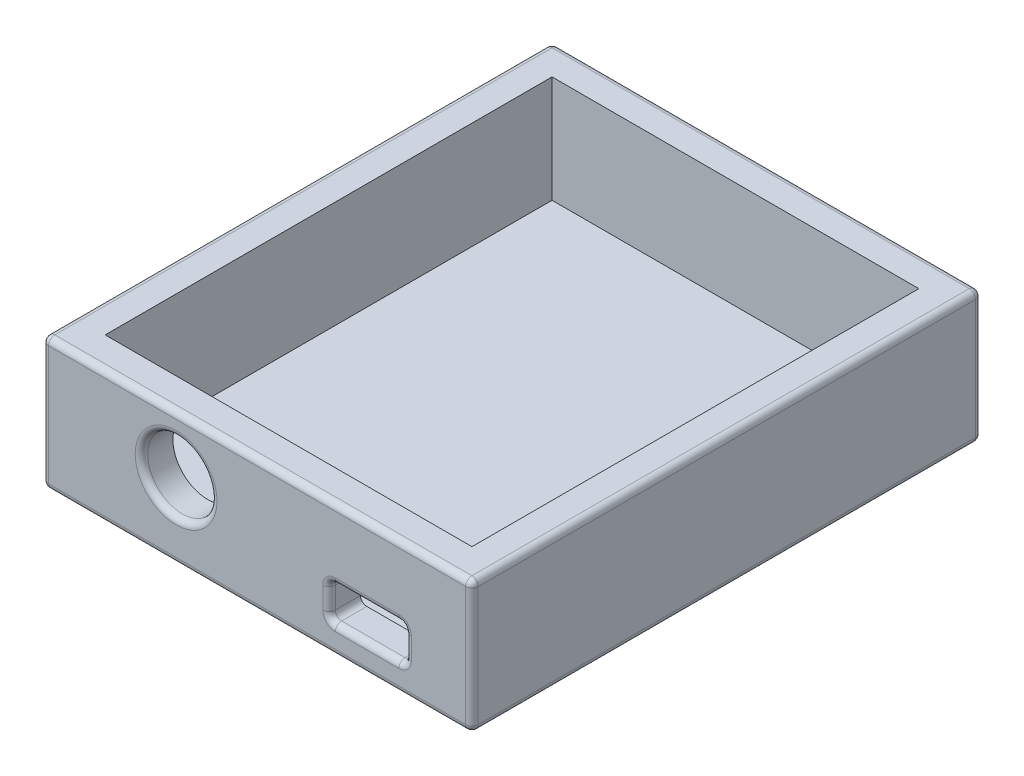
SolidWorks part; units mm, degrees
ref_plane "Alzado" through (0, 0, 0) normal (0, 0, 1) x (1, 0, 0)
ref_plane "Planta" through (0, 0, 0) normal (0, 1, 0) x (1, 0, 0)
ref_plane "Vista lateral" through (0, 0, 0) normal (1, 0, 0) x (0, 0, -1)
sketch "Croquis1" plane through (0, 29.5752, 0) normal (0, -1, 0) x (1, 0, 0)
  line L1 (-7.6603, 95.1114) -> (60.6797, 95.1114)
  line L2 (-7.6603, 95.1114) -> (-7.6603, 14.0314)
  line L3 (-7.6603, 14.0314) -> (60.6797, 14.0314)
  line L4 (60.6797, 95.1114) -> (60.6797, 14.0314)
  line L5 (-0.1603, 25.5954) -> (-0.1603, 90.1114) construction
  line L6 (53.1797, 90.1114) -> (53.1797, 24.0714) construction
  line L7 (48.0997, 21.5314) -> (15.0797, 21.5314) construction
  line L12 (-0.1603, 90.1114) -> (53.1797, 90.1114) construction
  point P6 (57.2525, 98.9534)
  point P11 (-7.6603, 95.9565)
  dimension "D1" = 5
  dimension "D2" = 7.5
  dimension "D3" = 7.5
  dimension "D4" = 7.5
extrude "Saliente-Extruir1" add sketch "Croquis1" along normal blind 4
sketch "Croquis2" plane through (0, 29.5752, 0) normal (0, 1, 0) x (1, 0, 0)
  line L0 (-2.6603, -19.0314) -> (-2.6603, -90.1114)
  line L1 (-2.6603, -90.1114) -> (55.6797, -90.1114)
  line L2 (55.6797, -90.1114) -> (55.6797, -19.0314)
  line L3 (55.6797, -19.0314) -> (-2.6603, -19.0314)
  line L4 (-7.6603, -14.0314) -> (-7.6603, -95.1114)
  line L5 (-7.6603, -95.1114) -> (60.6797, -95.1114)
  line L6 (60.6797, -95.1114) -> (60.6797, -14.0314)
  line L7 (60.6797, -14.0314) -> (-7.6603, -14.0314)
  line L8 (-7.6603, -14.0314) -> (-7.6603, -95.1114)
  line L9 (-7.6603, -95.1114) -> (60.6797, -95.1114)
  line L10 (60.6797, -95.1114) -> (60.6797, -14.0314)
  line L11 (60.6797, -14.0314) -> (-7.6603, -14.0314)
  dimension "D1" = 0
  dimension "D2" = 5
extrude "Saliente-Extruir2" add sketch "Croquis2" along normal blind 17
sketch "Croquis3" plane through (0, 0, 95.1114) normal (0, 0, 1) x (1, 0, 0)
  line L0 (42.0518, 33.9202) -> (48.0518, 33.9202) construction
  line L1 (37.9546, 35.4202) -> (50.0418, 35.4202)
  line L2 (37.9546, 35.4202) -> (37.9546, 29.9802)
  line L3 (37.9546, 29.9802) -> (50.0418, 29.9802)
  line L12 (50.0418, 35.4202) -> (50.0418, 29.9802)
  line L13 (45.2618, 30.9802) -> (47.3518, 30.9802) construction
  line L14 (38.9546, 32.8752) -> (38.9546, 32.6752) construction
  line L15 (49.0418, 32.8752) -> (49.0418, 32.6752) construction
  circle A0 centre (13.6167, 37.5502) radius 5.5
  dimension ".9" = 11
  dimension "D1" = 1.5
  dimension "D3" = 1
  dimension "D4" = 1
  dimension "D5" = 1
extrude "Cortar-Extruir1" cut sketch "Croquis3" against normal blind 8
fillet "Redondeo1" radius 1 4 edges at (37.9546, 35.4202, 92.6114) (50.0418, 35.4202, 92.6114) (50.0418, 29.9802, 92.6114) (37.9546, 29.9802, 92.6114)
fillet "Redondeo2" radius 1 21 edges at (60.6797, 25.5752, 54.5714) (60.6797, 46.5752, 54.5714) (26.5097, 25.5752, 95.1114) (26.5097, 46.5752, 95.1114) (19.1167, 37.5502, 95.1114) (49.7489, 30.2731, 95.1114) (50.0418, 32.7002, 95.1114) (49.7489, 35.1273, 95.1114) (43.9982, 35.4202, 95.1114) (38.2475, 35.1273, 95.1114) (37.9546, 32.7002, 95.1114) (38.2475, 30.2731, 95.1114) (43.9982, 29.9802, 95.1114) (-7.6603, 25.5752, 54.5714) (-7.6603, 46.5752, 54.5714) (26.5097, 25.5752, 14.0314) (60.6797, 36.0752, 14.0314) (26.5097, 46.5752, 14.0314) (-7.6603, 36.0752, 14.0314) (-7.6603, 36.0752, 95.1114) (60.6797, 36.0752, 95.1114)
